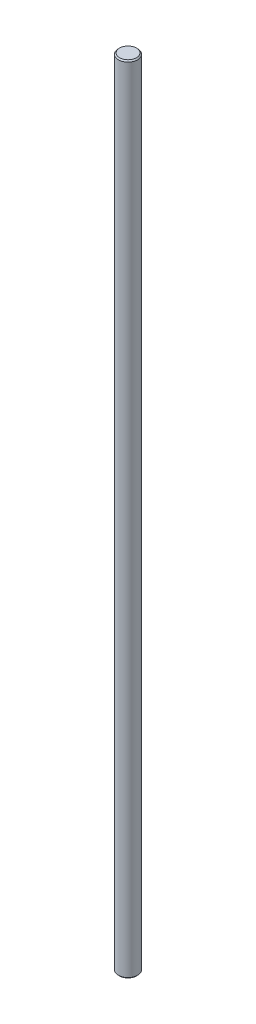
SolidWorks part; units mm, degrees
ref_plane "Front Plane" through (0, 0, 0) normal (0, 0, 1) x (1, 0, 0)
ref_plane "Top Plane" through (0, 0, 0) normal (0, 1, 0) x (1, 0, 0)
ref_plane "Right Plane" through (0, 0, 0) normal (1, 0, 0) x (0, 0, -1)
sketch "Sketch1" plane through (0, 0, 0) normal (0, 0, 1) x (1, 0, 0)
  line L0 (3.5, 330) -> (0, 330)
  line L1 (0, 330) -> (0, 0)
  line L2 (0, 0) -> (3.5, 0)
  line L3 (3.5, 0) -> (4, 0.5)
  line L4 (4, 0.5) -> (4, 329.5)
  line L5 (4, 329.5) -> (3.5, 330)
  line L6 (0, 330) -> (0, 0) construction
revolve "Revolve1" add sketch "Sketch1" angle 360 about L6
